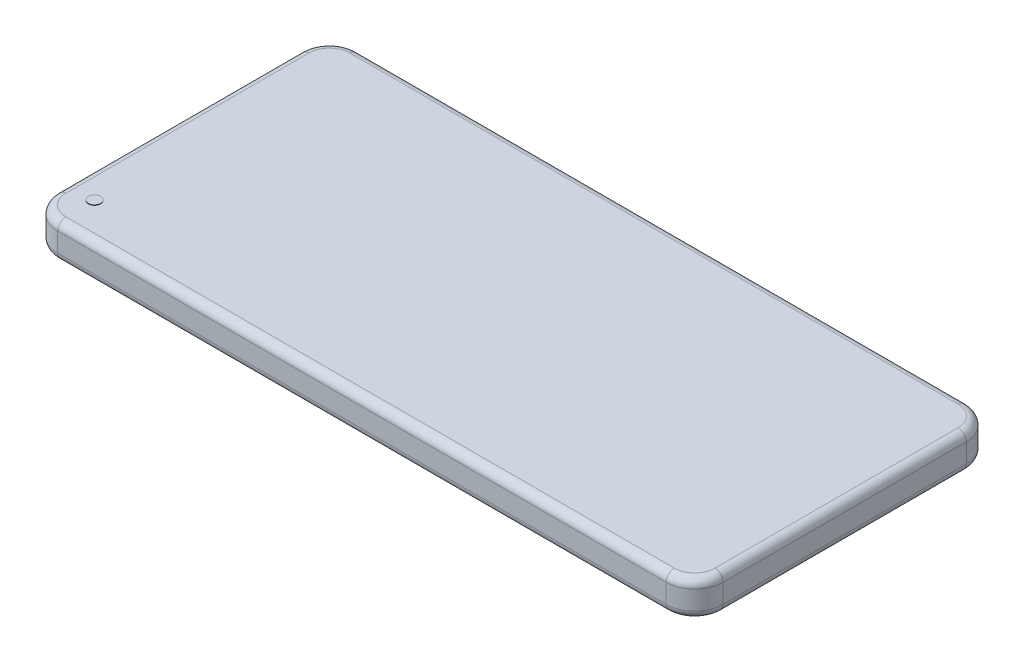
SolidWorks part; units mm, degrees
ref_plane "Front Plane" through (0, 0, 0) normal (0, 0, 1) x (1, 0, 0)
ref_plane "Top Plane" through (0, 0, 0) normal (0, 1, 0) x (1, 0, 0)
ref_plane "Right Plane" through (0, 0, 0) normal (1, 0, 0) x (0, 0, -1)
sketch "Sketch1" plane through (0, 0, 0) normal (0, 1, 0) x (1, 0, 0)
  line L1 (-81.6, -36.8) -> (81.6, -36.8)
  line L2 (-81.6, -36.8) -> (-81.6, 36.8)
  line L3 (-81.6, 36.8) -> (81.6, 36.8)
  line L4 (81.6, -36.8) -> (81.6, 36.8)
  line L5 (-81.6, -36.8) -> (81.6, 36.8) construction
  line L6 (-81.6, 36.8) -> (81.6, -36.8) construction
  point P0 (0, 0)
  dimension "D1" = 163.2
  dimension "D2" = 73.6
extrude "Boss-Extrude1" add sketch "Sketch1" along normal blind 8.7
fillet "Fillet1" radius 7 4 edges at (81.6, 4.35, 36.8) (81.6, 4.35, -36.8) (-81.6, 4.35, -36.8) (-81.6, 4.35, 36.8)
fillet "Fillet2" radius 2 8 edges at (-79.5497, 8.7, 34.7497) (-81.6, 8.7, 0) (-79.5497, 8.7, -34.7497) (0, 8.7, -36.8) (79.5497, 8.7, -34.7497) (81.6, 8.7, 0) (79.5497, 8.7, 34.7497) (0, 8.7, 36.8)
sketch "Sketch2" plane through (0, 8.7, 0) normal (0, 1, 0) x (1, 0, 0)
  line L0 (-74.6, -34.8) -> (74.6, -34.8) construction
  line L1 (-79.6, 29.8) -> (-79.6, -29.8) construction
  circle A0 centre (-74.6, -27.8) radius 1.5
  dimension "D1" = 3
  dimension "D2" = 7
  dimension "D3" = 5
extrude "Boss-Extrude2" add sketch "Sketch2" along normal blind 0.1
fillet "Fillet3" radius 2 8 edges at (79.5497, 0, -34.7497) (0, 0, -36.8) (-79.5497, 0, -34.7497) (-81.6, 0, 0) (-79.5497, 0, 34.7497) (0, 0, 36.8) (79.5497, 0, 34.7497) (81.6, 0, 0)
sketch "Sketch3" plane through (0, 0, 0) normal (0, -1, 0) x (1, 0, 0)
  line L0 (-79.6, 29.8) -> (-79.6, -29.8) construction
  line L1 (-34.6, -6.8) -> (-74.6, -6.8)
  line L2 (-34.6, -6.8) -> (-34.6, -28.8)
  line L3 (-34.6, -28.8) -> (-74.6, -28.8)
  line L4 (-74.6, -6.8) -> (-74.6, -28.8)
  line L5 (-34.6, -6.8) -> (-74.6, -28.8) construction
  line L6 (-34.6, -28.8) -> (-74.6, -6.8) construction
  line L7 (74.6, -36.8) -> (-74.6, -36.8) construction
  point P0 (-54.6, -17.8)
  dimension "D1" = 22
  dimension "D2" = 40
  dimension "D3" = 5
  dimension "D4" = 8
extrude "Boss-Extrude3" add sketch "Sketch3" along normal blind 1
fillet "Fillet4" radius 4 4 edges at (-34.6, -0.5, -28.8) (-34.6, -0.5, -6.8) (-74.6, -0.5, -28.8) (-74.6, -0.5, -6.8)
sketch "Sketch4" plane through (0, -1, 0) normal (0, -1, 0) x (1, 0, 0)
  line L8 (-70.6, -27.8) -> (-38.6, -27.8)
  line L9 (-35.6, -24.8) -> (-35.6, -10.8)
  line L10 (-38.6, -7.8) -> (-70.6, -7.8)
  line L11 (-73.6, -10.8) -> (-73.6, -24.8)
  line L12 (-70.6, -27.8) -> (-38.6, -27.8)
  line L13 (-35.6, -24.8) -> (-35.6, -10.8)
  line L14 (-38.6, -7.8) -> (-70.6, -7.8)
  line L15 (-73.6, -10.8) -> (-73.6, -24.8)
  arc A8 (-38.6, -27.8) -> (-35.6, -24.8) centre (-38.6, -24.8) ccw
  arc A9 (-35.6, -10.8) -> (-38.6, -7.8) centre (-38.6, -10.8) ccw
  arc A10 (-70.6, -7.8) -> (-73.6, -10.8) centre (-70.6, -10.8) ccw
  arc A11 (-73.6, -24.8) -> (-70.6, -27.8) centre (-70.6, -24.8) ccw
  arc A12 (-38.6, -27.8) -> (-35.6, -24.8) centre (-38.6, -24.8) ccw
  arc A13 (-35.6, -10.8) -> (-38.6, -7.8) centre (-38.6, -10.8) ccw
  arc A14 (-70.6, -7.8) -> (-73.6, -10.8) centre (-70.6, -10.8) ccw
  arc A15 (-73.6, -24.8) -> (-70.6, -27.8) centre (-70.6, -24.8) ccw
  dimension "D1" = 1
extrude "Cut-Extrude1" cut sketch "Sketch4" against normal up to surface (1 mm away) up to face at (0, 0, 0)
sketch "Sketch5" plane through (0, 0, 0) normal (0, -1, 0) x (-1, 0, 0)
  line L0 (38.6, 27.8) -> (70.6, 27.8) construction
  line L1 (73.6, 10.8) -> (73.6, 24.8) construction
  line L2 (40.6, 22.05) -> (40.6, 13.55) construction
  line L3 (35.6, 10.8) -> (35.6, 24.8) construction
  line L4 (66.6, 20.8) -> (59.6, 12.3147) construction
  line L5 (59.6, 12.3147) -> (52.6, 20.8) construction
  circle A0 centre (66.6, 20.8) radius 5
  circle A1 centre (52.6, 20.8) radius 5
  circle A2 centre (40.6, 22.05) radius 2.5
  circle A3 centre (40.6, 13.55) radius 2.5
  circle A4 centre (59.6, 12.3147) radius 2
  point P10 (40.6, 17.8)
  point P11 (35.6, 17.8)
  dimension "D1" = 10
  dimension "D2" = 10
  dimension "D3" = 5
  dimension "D4" = 5
  dimension "D5" = 4
  dimension "D11" = 11
  dimension "D6" = 7
  dimension "D7" = 7
  dimension "D8" = 14
  dimension "D9" = 8.5
  dimension "D10" = 5
extrude "Boss-Extrude4" add sketch "Sketch5" along normal blind 1
sketch "Sketch6" plane through (0, -1, 0) normal (0, -1, 0) x (1, 0, 0)
  circle A0 centre (-66.6, -20.8) radius 4
  circle A1 centre (-52.6, -20.8) radius 4
  circle A2 centre (-40.6, -22.05) radius 1.4
  circle A3 centre (-40.6, -13.55) radius 1.4
  circle A4 centre (-59.6, -12.3147) radius 1
  dimension "D1" = 8
  dimension "D2" = 8
  dimension "D3" = 2.8
  dimension "D4" = 2
extrude "Boss-Extrude5" add sketch "Sketch6" along normal blind 0.1
